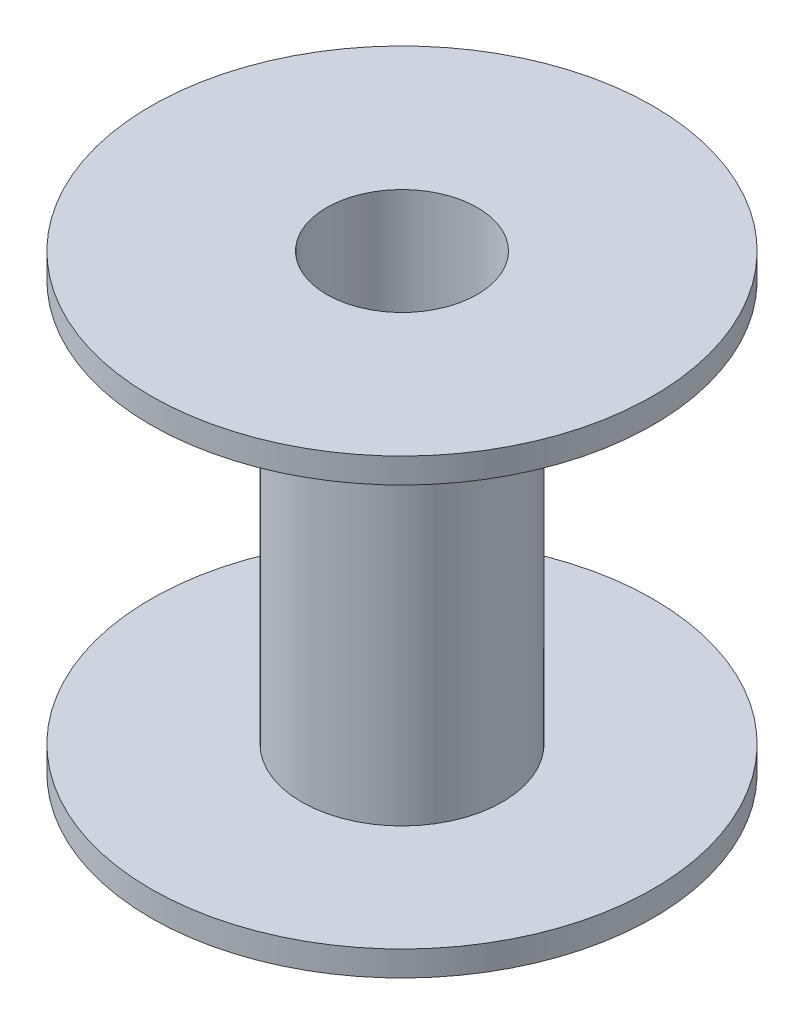
SolidWorks part; units mm, degrees
ref_plane "Front Plane" through (0, 0, 0) normal (0, 0, 1) x (1, 0, 0)
ref_plane "Top Plane" through (0, 0, 0) normal (0, 1, 0) x (1, 0, 0)
ref_plane "Right Plane" through (0, 0, 0) normal (1, 0, 0) x (0, 0, -1)
sketch "Sketch1" plane through (0, 0, 0) normal (1, 0, 0) x (0, 0, -1)
  line L0 (0, 20.0281) -> (0, -51.7974) construction
  line L1 (-7.5, 1.5978) -> (-25, 1.5978)
  line L7 (-25, -43.4022) -> (-7.5, -43.4022)
  line L8 (-7.5, -43.4022) -> (-7.5, 1.5978)
  line L9 (-25, 1.5978) -> (-25, -0.9022)
  line L10 (-25, -0.9022) -> (-10, -0.9022)
  line L11 (-10, -0.9022) -> (-10, -40.9022)
  line L12 (-10, -40.9022) -> (-25, -40.9022)
  line L13 (-25, -40.9022) -> (-25, -43.4022)
  point P5 (0, -51.7974)
  point P12 (0, 20.0281)
  dimension "D1" = 15
  dimension "D2" = 45
  dimension "D3" = 40
  dimension "D4" = 50
  dimension "D5" = 45
  dimension "D6" = 2.5
  dimension "D7" = 2.5
  dimension "D8" = 2.5
  dimension "D9" = 17.5
  dimension "D10" = 20
revolve "Revolve1" add sketch "Sketch1" angle 360 about L0
